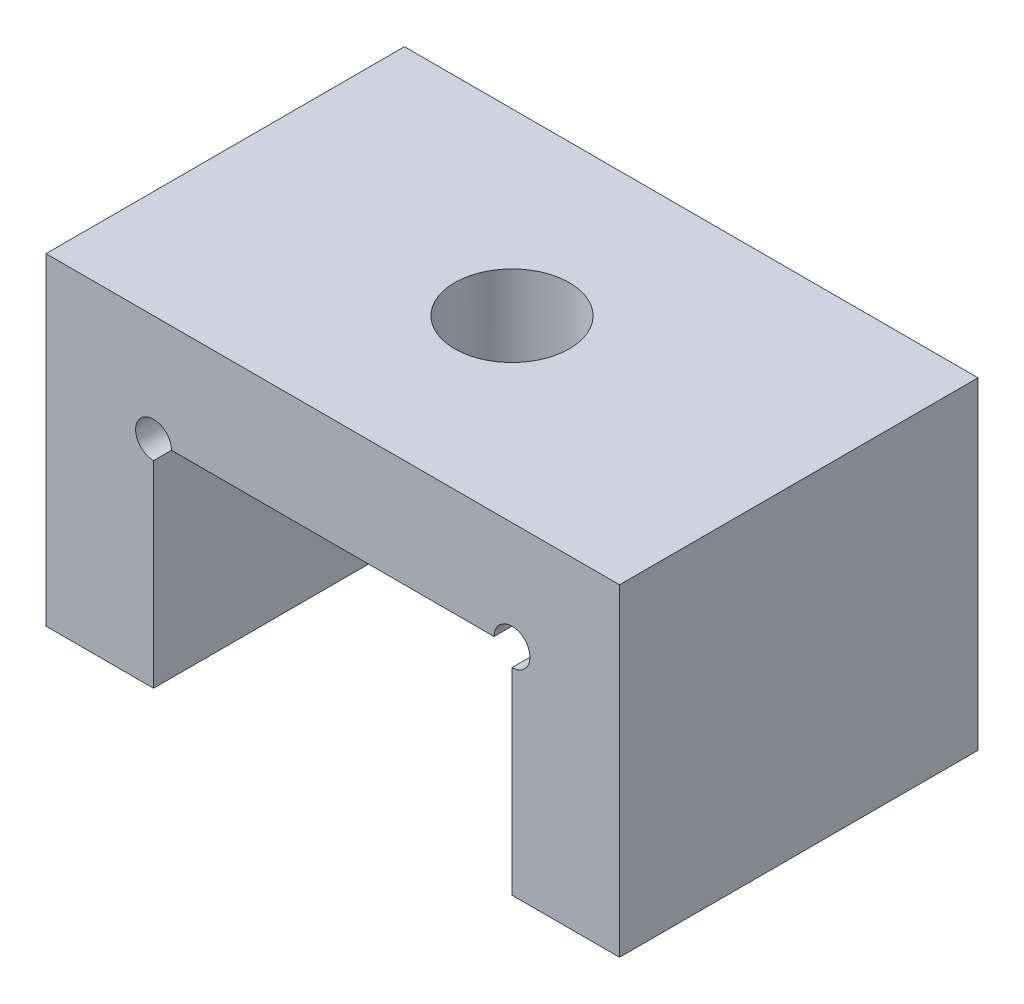
SolidWorks part; units mm, degrees
ref_plane "前视基准面" through (0, 0, 0) normal (0, 0, 1) x (1, 0, 0)
ref_plane "上视基准面" through (0, 0, 0) normal (0, 1, 0) x (1, 0, 0)
ref_plane "右视基准面" through (0, 0, 0) normal (1, 0, 0) x (0, 0, -1)
other "Configuration Table"
sketch "草图1" plane through (0, 0, 0) normal (0, 0, 1) x (1, 0, 0)
  line L0 (0, 0) -> (-8, 0)
  line L1 (-8, 0) -> (-8, -9)
  line L2 (-8, -9) -> (-5, -9)
  line L3 (-5, -9) -> (-5, -3)
  line L4 (-5, -3) -> (5, -3)
  line L5 (5, -3) -> (5, -9)
  line L6 (5, -9) -> (8, -9)
  line L7 (8, -9) -> (8, 0)
  line L8 (8, 0) -> (0, 0)
  line L9 (0, 0) -> (0, 6.3245) construction
  dimension "D1" = 16
  dimension "D2" = 3
  dimension "D3" = 3
  dimension "D4" = 6
  dimension "D5" = 6
  dimension "D6" = 9
extrude "凸台-拉伸1" add sketch "草图1" along normal blind 10
sketch "草图2" plane through (0, 0, 0) normal (0, 1, 0) x (1, 0, 0)
  line L0 (-8, -5) -> (8, -5) construction
  line L1 (-8, -10) -> (-8, 0) construction
  line L2 (8, -10) -> (8, 0) construction
  line L3 (0, 0) -> (0, -10) construction
  line L4 (8, -10) -> (-8, -10) construction
  circle A0 centre (0, -5) radius 1.6
  dimension "D1" = 3.2
extrude "切除-拉伸1" cut sketch "草图2" against normal through all
sketch "草图5" plane through (0, 0, 10) normal (0, 0, 1) x (1, 0, 0)
  circle A0 centre (-5, -3) radius 0.5
  circle A1 centre (5, -3) radius 0.5
  dimension "D1" = 1
  dimension "D2" = 1
extrude "切除-拉伸2" cut sketch "草图5" against normal through all
